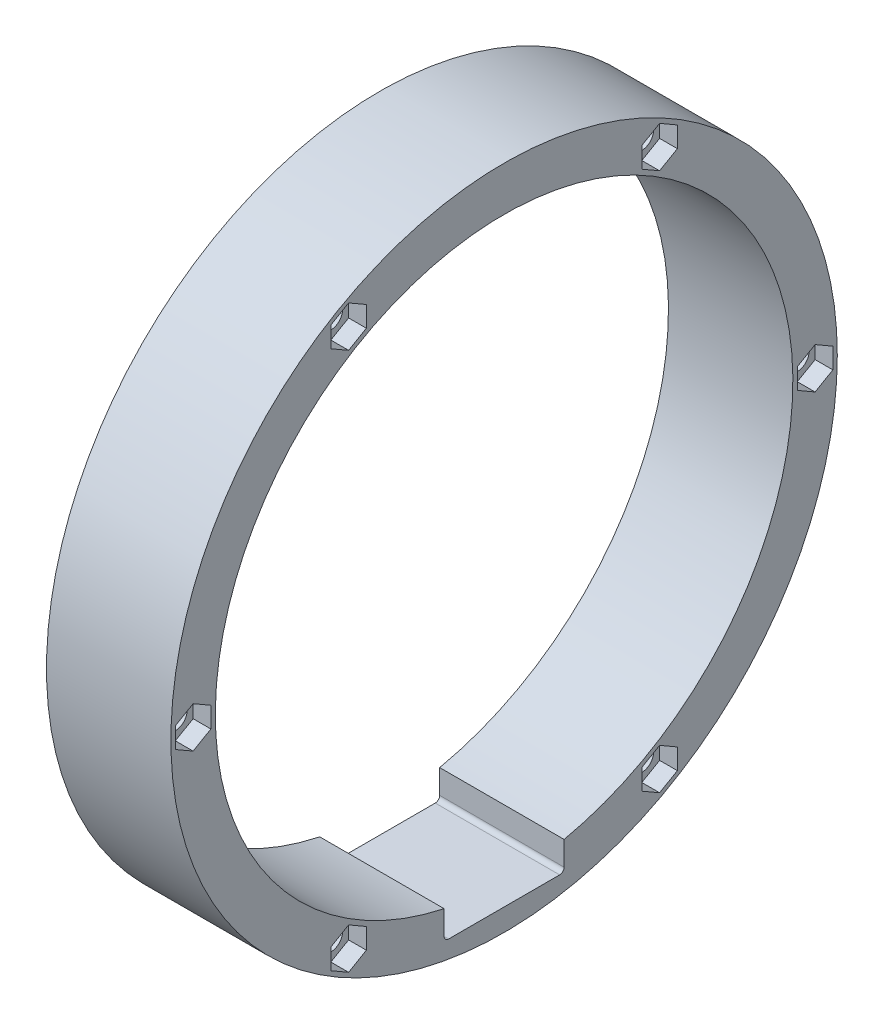
SolidWorks part; units mm, degrees
ref_plane "Front Plane" through (0, 0, 0) normal (0, 0, 1) x (1, 0, 0)
ref_plane "Top Plane" through (0, 0, 0) normal (0, 1, 0) x (1, 0, 0)
ref_plane "Right Plane" through (0, 0, 0) normal (1, 0, 0) x (0, 0, -1)
sketch "Sketch1" plane through (0, 0, 0) normal (1, 0, 0) x (0, 0, -1)
  circle A0 centre (0, 0) radius 75
  circle A1 centre (0, 0) radius 65
  dimension "D1" = 150
  dimension "D2" = 130
extrude "Boss-Extrude1" add sketch "Sketch1" along normal blind 28
sketch "Sketch2" plane through (28, 0, 0) normal (1, 0, 0) x (0, 0, -1)
  line L0 (0, -34.8517) -> (0, -97.703) construction
  line L1 (-13.5, -51.894) -> (13.5, -51.894)
  line L2 (-13.5, -51.894) -> (-13.5, -69)
  line L3 (-12.5, -70) -> (12.5, -70)
  line L4 (13.5, -51.894) -> (13.5, -69)
  circle A1 centre (0, 0) radius 75 construction
  arc A2 (-13.5, -69) -> (-12.5, -70) centre (-12.5, -69) ccw
  arc A3 (13.5, -69) -> (12.5, -70) centre (12.5, -69) cw
  point P6 (0, -51.894)
  point P10 (0, -75)
  dimension "D2" = 1
  dimension "D3" = 1
  dimension "D1" = 5
  dimension "D4" = 27
extrude "Cut-Extrude1" cut sketch "Sketch2" against normal up to next
sketch "Sketch3" plane through (28, 0, 0) normal (1, 0, 0) x (0, 0, -1)
  line L0 (-94.7404, 0) -> (95.285, 0) construction
  circle A0 centre (-70, 0) radius 2.65
  circle A1 centre (-35, 60.6218) radius 2.65
  circle A2 centre (35, 60.6218) radius 2.65
  circle A3 centre (70, 0) radius 2.65
  circle A4 centre (35, -60.6218) radius 2.65
  circle A5 centre (-35, -60.6218) radius 2.65
  point P17 (0, 0)
  dimension "D1" = 5.3
  dimension "D2" = 70
  dimension "D3" = 6
extrude "Cut-Extrude2" cut sketch "Sketch3" against normal up to next
sketch "Sketch4" plane through (28, 0, 0) normal (1, 0, 0) x (0, 0, -1)
  line L0 (-39, 58.3124) -> (-35, 56.003)
  line L1 (-70, -4.6188) -> (-66, -2.3094)
  line L2 (-66, -2.3094) -> (-66, 2.3094)
  line L3 (-66, 2.3094) -> (-70, 4.6188)
  line L4 (-70, 4.6188) -> (-74, 2.3094)
  line L5 (-74, 2.3094) -> (-74, -2.3094)
  line L6 (-74, -2.3094) -> (-70, -4.6188)
  line L7 (-35, 56.003) -> (-31, 58.3124)
  line L8 (-31, 58.3124) -> (-31, 62.9312)
  line L9 (-31, 62.9312) -> (-35, 65.2406)
  line L10 (-35, 65.2406) -> (-39, 62.9312)
  line L11 (-39, 62.9312) -> (-39, 58.3124)
  line L12 (31, 62.9312) -> (31, 58.3124)
  line L13 (31, 58.3124) -> (35, 56.003)
  line L14 (35, 56.003) -> (39, 58.3124)
  line L15 (39, 58.3124) -> (39, 62.9312)
  line L16 (39, 62.9312) -> (35, 65.2406)
  line L17 (35, 65.2406) -> (31, 62.9312)
  line L18 (70, 4.6188) -> (66, 2.3094)
  line L19 (66, 2.3094) -> (66, -2.3094)
  line L20 (66, -2.3094) -> (70, -4.6188)
  line L21 (70, -4.6188) -> (74, -2.3094)
  line L22 (74, -2.3094) -> (74, 2.3094)
  line L23 (74, 2.3094) -> (70, 4.6188)
  line L24 (39, -58.3124) -> (35, -56.003)
  line L25 (35, -56.003) -> (31, -58.3124)
  line L26 (31, -58.3124) -> (31, -62.9312)
  line L27 (31, -62.9312) -> (35, -65.2406)
  line L28 (35, -65.2406) -> (39, -62.9312)
  line L29 (39, -62.9312) -> (39, -58.3124)
  line L30 (-31, -62.9312) -> (-31, -58.3124)
  line L31 (-31, -58.3124) -> (-35, -56.003)
  line L32 (-35, -56.003) -> (-39, -58.3124)
  line L33 (-39, -58.3124) -> (-39, -62.9312)
  line L34 (-39, -62.9312) -> (-35, -65.2406)
  line L35 (-35, -65.2406) -> (-31, -62.9312)
  circle A0 centre (-70, 0) radius 4 construction
  circle A1 centre (-35, 60.6218) radius 4 construction
  circle A2 centre (35, 60.6218) radius 4 construction
  circle A3 centre (70, 0) radius 4 construction
  circle A4 centre (35, -60.6218) radius 4 construction
  circle A5 centre (-35, -60.6218) radius 4 construction
  point P52 (0, 0)
  dimension "D1" = 8
  dimension "D2" = 6
extrude "Cut-Extrude3" cut sketch "Sketch4" against normal blind 4
